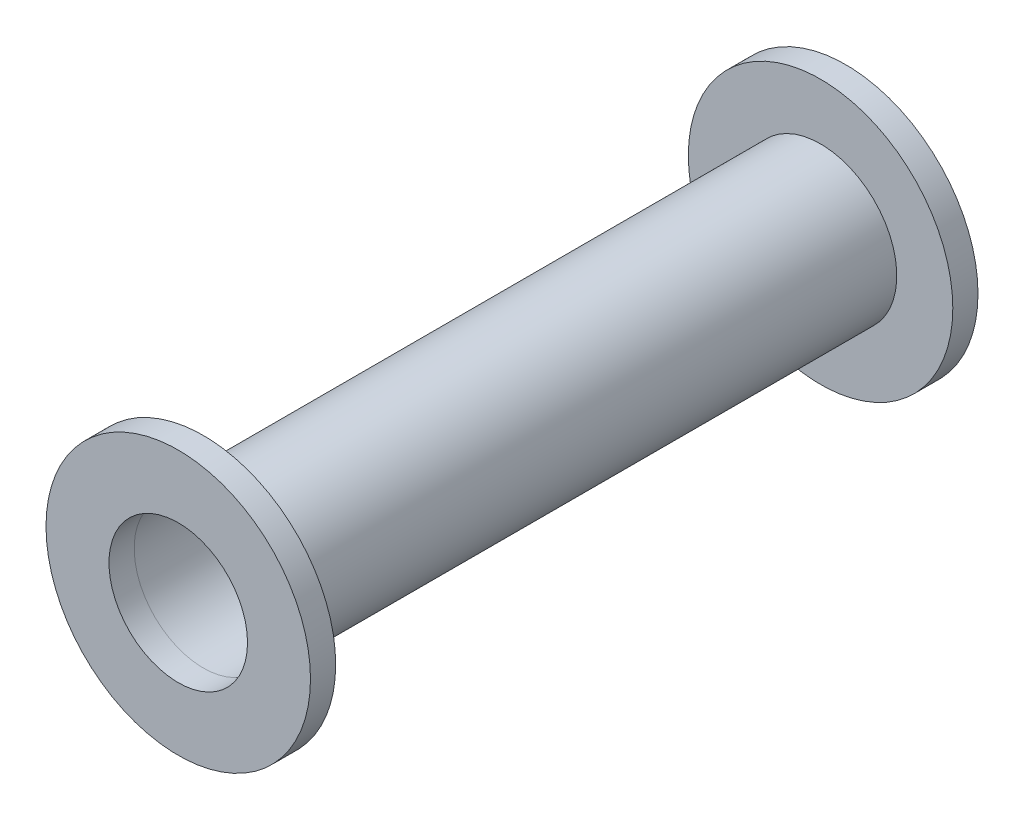
SolidWorks part; units mm, degrees
ref_plane "Front Plane" through (0, 0, 0) normal (0, 0, 1) x (1, 0, 0)
ref_plane "Top Plane" through (0, 0, 0) normal (0, 1, 0) x (1, 0, 0)
ref_plane "Right Plane" through (0, 0, 0) normal (1, 0, 0) x (0, 0, -1)
sketch "Sketch1" plane through (0, 0, 0) normal (0, 0, 1) x (1, 0, 0)
  circle A0 centre (0, 0) radius 5.55
  circle A1 centre (0, 0) radius 6.05
  dimension "D1" = 11.1
  dimension "D2" = 12.1
extrude "Extrude1" add sketch "Sketch1" along normal blind 49
sketch "Sketch2" plane through (0, 0, 49) normal (0, 0, 1) x (1, 0, 0)
  circle A0 centre (0, 0) radius 5.5
  circle A1 centre (0, 0) radius 10.5
  dimension "D1" = 21
  dimension "D2" = 11
extrude "Extrude3" add sketch "Sketch2" along normal blind 2
sketch "Sketch3" plane through (0, 0, 0) normal (0, 0, -1) x (-1, 0, 0)
  circle A0 centre (0, 0) radius 5.5
  circle A1 centre (0, 0) radius 10.5
  dimension "D1" = 11
  dimension "D2" = 21
extrude "Extrude4" add sketch "Sketch3" along normal blind 2
